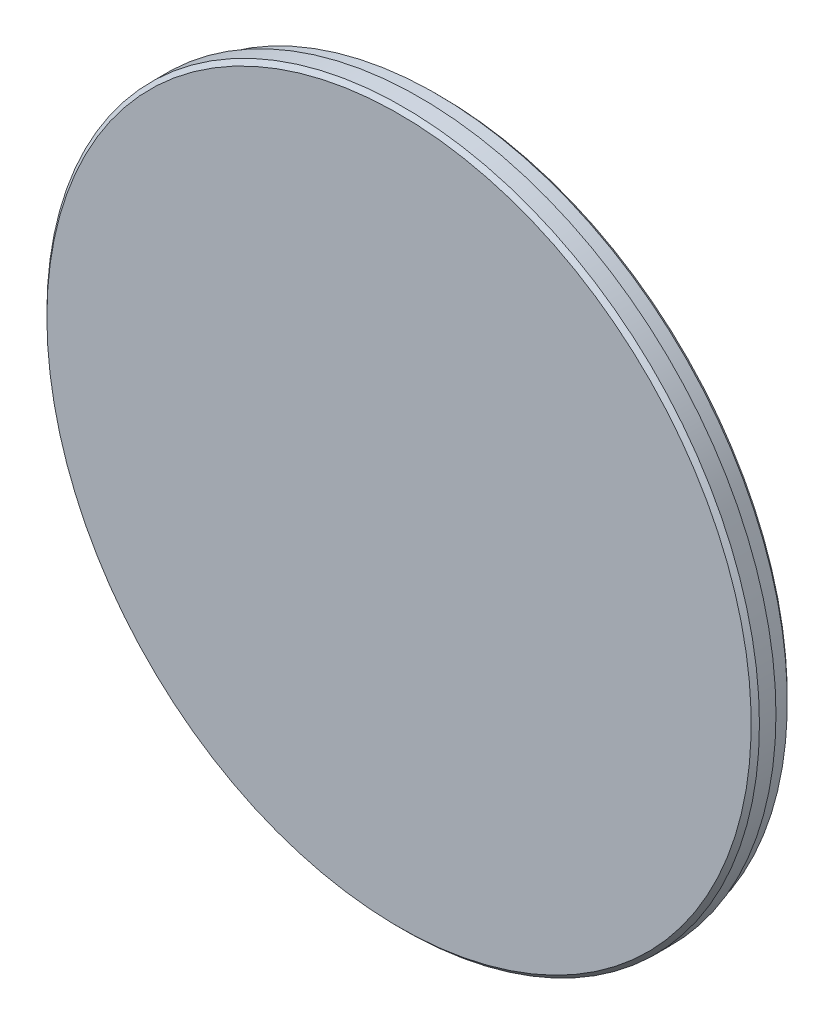
SolidWorks part; units mm, degrees
ref_plane "Front Plane" through (0, 0, 0) normal (0, 0, 1) x (1, 0, 0)
ref_plane "Top Plane" through (0, 0, 0) normal (0, 1, 0) x (1, 0, 0)
ref_plane "Right Plane" through (0, 0, 0) normal (1, 0, 0) x (0, 0, -1)
sketch "Sketch1" plane through (0, 0, 0) normal (0, 0, 1) x (1, 0, 0)
  circle A0 centre (0, 0) radius 17.25
  dimension "D1" = 34.5
extrude "Boss-Extrude1" add sketch "Sketch1" against normal blind 1
sketch "Sketch2" plane through (0, 0, -1) normal (0, 0, -1) x (-1, 0, 0)
  circle A0 centre (0, 0) radius 17
  dimension "D1" = 34
extrude "Boss-Extrude2" add sketch "Sketch2" along normal blind 1
chamfer "Chamfer1" distance 0.2 angle 45 2 edges at (-17, 0, -2) (17.25, 0, 0)
